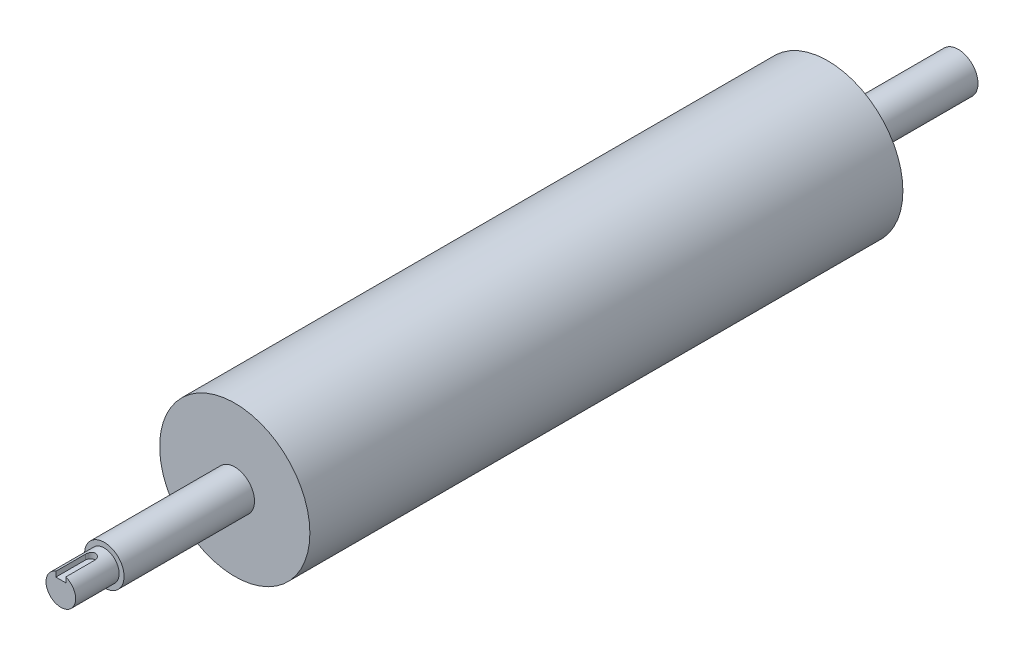
SolidWorks part; units mm, degrees
material "45钢"
ref_plane "前视基准面" through (0, 0, 0) normal (0, 0, 1) x (1, 0, 0)
ref_plane "上视基准面" through (0, 0, 0) normal (0, 1, 0) x (1, 0, 0)
ref_plane "右视基准面" through (0, 0, 0) normal (1, 0, 0) x (0, 0, -1)
sketch "草图1" plane through (0, 0, 0) normal (0, 0, 1) x (1, 0, 0)
  circle A0 centre (0, 0) radius 38
  dimension "D1" = 76
extrude "凸台-拉伸1" add sketch "草图1" along normal mid plane 300
sketch "草图2" plane through (0, 0, 150) normal (0, 0, 1) x (1, 0, 0)
  circle A0 centre (0, 0) radius 10
  dimension "D1" = 20
extrude "凸台-拉伸2" add sketch "草图2" along normal blind 66
mirror "镜向1" about plane through (0, 0, 0) normal (0, 0, 1) of "凸台-拉伸2"
sketch "草图3" plane through (0, 0, 216) normal (0, 0, 1) x (1, 0, 0)
  circle A0 centre (0, 0) radius 7.5
  dimension "D1" = 15
extrude "凸台-拉伸3" add sketch "草图3" along normal blind 22
sketch "草图4" plane through (0, 0, 0) normal (0, 1, 0) x (1, 0, 0)
  line L0 (0, -238) -> (0, -223) construction
  line L1 (-7.5, -238) -> (7.5, -238) construction
  line L2 (-2.5, -238) -> (-2.5, -223)
  line L3 (2.5, -238) -> (2.5, -223)
  arc A0 (-2.5, -238) -> (2.5, -238) centre (0, -238) ccw
  arc A1 (2.5, -223) -> (-2.5, -223) centre (0, -223) ccw
  point P5 (0, -230.5)
  dimension "D1" = 5
  dimension "D2" = 15
extrude "切除-拉伸1" cut sketch "草图4" against normal blind 3 from offset 7.5
